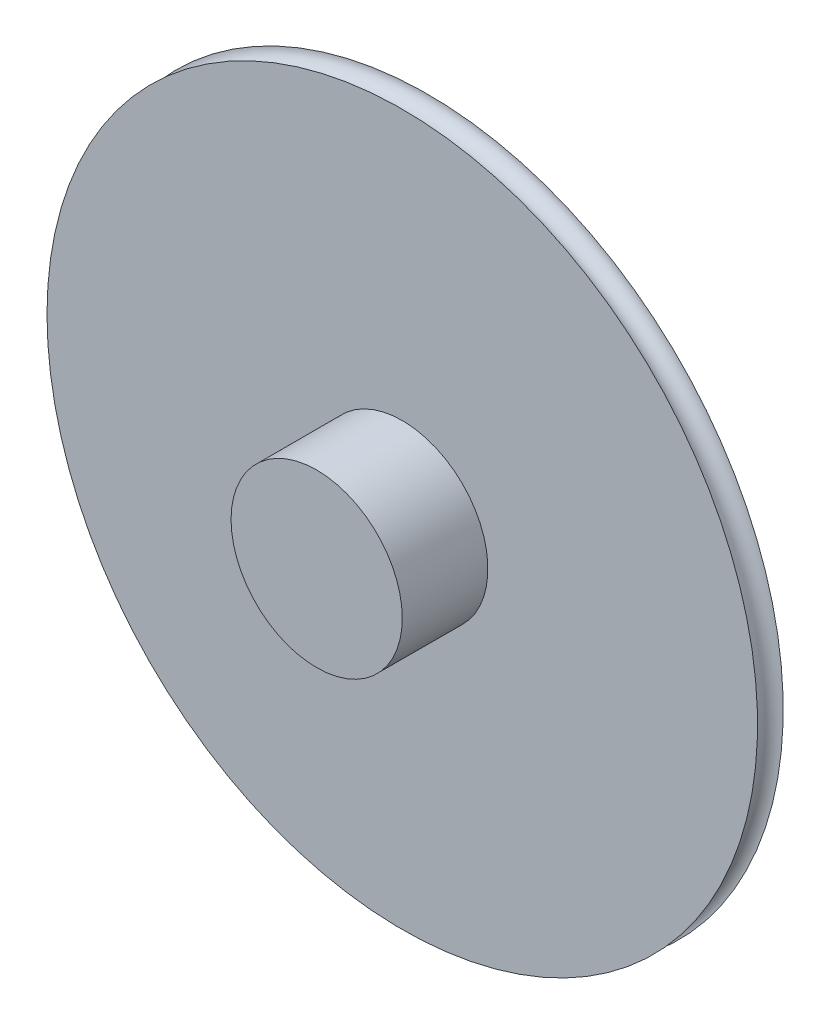
SolidWorks part; units mm, degrees
ref_plane "Front Plane" through (0, 0, 0) normal (0, 0, 1) x (1, 0, 0)
ref_plane "Top Plane" through (0, 0, 0) normal (0, 1, 0) x (1, 0, 0)
ref_plane "Right Plane" through (0, 0, 0) normal (1, 0, 0) x (0, 0, -1)
sketch "Sketch1" plane through (0, 0, 0) normal (0, 1, 0) x (1, 0, 0)
  line L0 (40, 1.5) -> (41.5, 1.5)
  line L1 (0, 1.5) -> (40, 1.5)
  line L2 (0, 1.5) -> (0, -1.5)
  line L3 (0, -1.5) -> (40, -1.5)
  line L4 (40, 1.5) -> (40, -1.5) construction
  line L7 (41.5, -1.5) -> (40, -1.5)
  arc A2 (41.5, 1.5) -> (41.5, -1.5) centre (41.5, 0) ccw
  point P4 (0, 0)
  point P9 (42.9876, 1.5)
  point P10 (41.567, -1.5)
  point P11 (0, 0)
  dimension "D1" = 3
  dimension "D2" = 40
revolve "Revolve2" add sketch "Sketch1" angle 360 about L2
sketch "Sketch2" plane through (0, 0, 1.5) normal (0, 0, 1) x (1, 0, 0)
  circle A0 centre (0, 0) radius 10
  dimension "D1" = 20
extrude "Boss-Extrude1" add sketch "Sketch2" along normal blind 10
